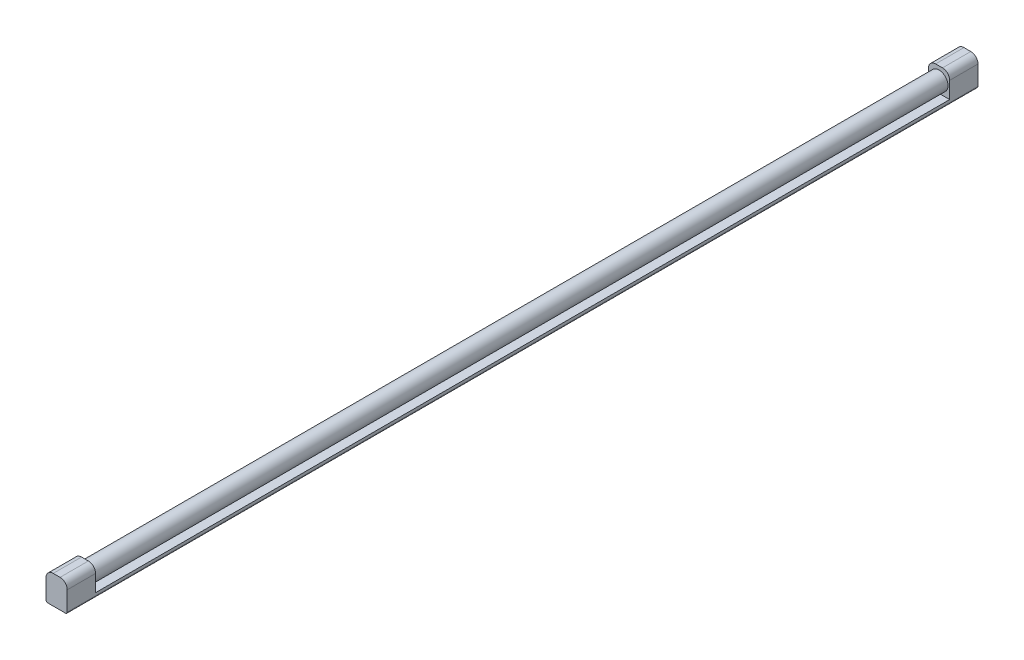
SolidWorks part; units mm, degrees
material "C-Glass Fiber"
ref_plane "Front Plane" through (0, 0, 0) normal (0, 0, 1) x (1, 0, 0)
ref_plane "Top Plane" through (0, 0, 0) normal (0, 1, 0) x (1, 0, 0)
ref_plane "Right Plane" through (0, 0, 0) normal (1, 0, 0) x (0, 0, -1)
sketch "Sketch1" plane through (0, 0, 0) normal (0, 0, 1) x (1, 0, 0)
  line L1 (0, 0) -> (30, 0)
  line L2 (0, 0) -> (0, 40)
  line L3 (0, 40) -> (30, 40)
  line L4 (30, 0) -> (30, 40)
  dimension "D1" = 30
  dimension "D2" = 40
extrude "Boss-Extrude1" add sketch "Sketch1" along normal blind 40
fillet "Fillet1" radius 10.16 2 edges at (30, 40, 20) (0, 40, 20)
fillet "Fillet2" radius 2.54 2 edges at (0, 0, 20) (30, 0, 20)
sketch "Sketch3" plane through (0, 0, 40) normal (0, 0, 1) x (1, 0, 0)
  line L0 (15, 40) -> (15, 15.2957) construction
  line L1 (19.84, 40) -> (10.16, 40) construction
  circle A0 centre (15, 22.22) radius 12.7
  dimension "D1" = 25.4
  dimension "D2" = 17.78
extrude "Boss-Extrude2" add sketch "Sketch3" along normal blind 1206
sketch "Sketch6" plane through (0, 0, 1246) normal (0, 0, 1) x (1, 0, 0)
  line L1 (0, 0) -> (30, 0)
  line L2 (0, 0) -> (0, 40)
  line L3 (0, 40) -> (30, 40)
  line L4 (30, 0) -> (30, 40)
extrude "Boss-Extrude3" add sketch "Sketch6" along normal blind 40
fillet "Fillet3" radius 10.16 2 edges at (30, 40, 1266) (0, 40, 1266)
fillet "Fillet4" radius 2.54 2 edges at (0, 0, 1266) (30, 0, 1266)
sketch "Sketch7" plane through (0, 0, 40) normal (0, 0, 1) x (1, 0, 0)
  line L0 (30, 2.54) -> (30, 29.84) construction
  line L1 (0, 0) -> (30, 0)
  line L2 (0, 0) -> (0, 6.35)
  line L3 (0, 6.35) -> (30, 6.35)
  line L4 (30, 0) -> (30, 6.35)
  dimension "D1" = 6.35
extrude "Boss-Extrude4" add sketch "Sketch7" along direction (0, 0, -1) on the side of the normal up to surface (1206 mm away)
fillet "Fillet5" radius 2.54 2 edges at (30, 0, 643) (0, 0, 643)
